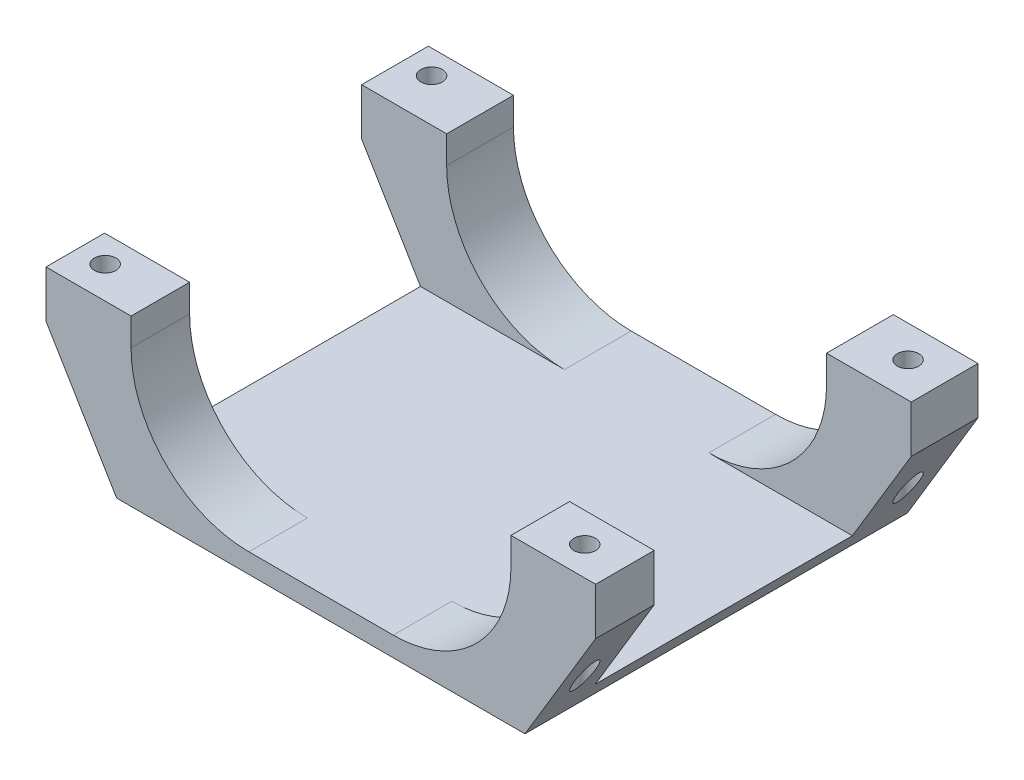
SolidWorks part; units mm, degrees
ref_plane "Front Plane" through (0, 0, 0) normal (0, 0, 1) x (1, 0, 0)
ref_plane "Top Plane" through (0, 0, 0) normal (0, 1, 0) x (1, 0, 0)
ref_plane "Right Plane" through (0, 0, 0) normal (1, 0, 0) x (0, 0, -1)
sketch "Sketch1" plane through (0, 0, 0) normal (0, 1, 0) x (1, 0, 0)
  line L1 (0, 0) -> (139.9914, 0)
  line L2 (0, 0) -> (0, 97.3933)
  line L3 (0, 97.3933) -> (139.9914, 97.3933)
  line L4 (139.9914, 0) -> (139.9914, 97.3933)
extrude "PiCover" add sketch "Sketch1" along normal blind 40 and the other way blind 2
sketch "Sketch2" plane through (0, 40, 0) normal (0, 1, 0) x (1, 0, 0)
  line L0 (139.9914, 97.3933) -> (0, 97.3933) construction
  line L1 (21.6644, 97.3933) -> (118.4243, 97.3933)
  line L2 (21.6644, 97.3933) -> (21.6644, -0.7263)
  line L3 (21.6644, -0.7263) -> (118.4243, -0.7263)
  line L4 (118.4243, 97.3933) -> (118.4243, -0.7263)
extrude "OpeningForPi" cut sketch "Sketch2" against normal blind 37
sketch "Sketch4" plane through (0, -2, 0) normal (0, -1, 0) x (1, 0, 0)
  line L0 (139.9914, -97.3933) -> (0, -97.3933) construction
  line L1 (139.9914, 0) -> (121.9914, 0)
  line L2 (139.9914, 0) -> (139.9914, -97.3933)
  line L3 (139.9914, -97.3933) -> (121.9914, -97.3933)
  line L4 (121.9914, 0) -> (121.9914, -97.3933)
  line L5 (0, 0) -> (139.9914, 0) construction
  line L6 (0, -97.3933) -> (18, -97.3933)
  line L7 (0, -97.3933) -> (0, 0)
  line L8 (0, 0) -> (18, 0)
  line L9 (18, -97.3933) -> (18, 0)
extrude "CutAwaysThatDefineScrewPlates" cut sketch "Sketch4" against normal blind 30
sketch "Sketch11" plane through (0, 0, 0) normal (0, 0, 1) x (1, 0, 0)
  line L0 (0, 28) -> (18, 28)
  line L1 (18, 28) -> (18, -2)
  line L2 (18, -2) -> (0, 28)
  line L3 (139.9914, 28) -> (121.9914, 28)
  line L4 (121.9914, 28) -> (121.9914, -2)
  line L5 (121.9914, -2) -> (139.9914, 28)
extrude "Boss-Extrude1" add sketch "Sketch11" against normal up to surface (97.3933 mm away) up to face at (70.0119, 22.8333, -97.3933)
sketch "Sketch6" plane through (21.6644, 0, 0) normal (1, 0, 0) x (0, 0, -1)
  line L0 (97.3933, 3) -> (0, 3) construction
  line L1 (80.3904, 3) -> (14.92, 3)
  line L2 (80.3904, 3) -> (80.3904, 40)
  line L3 (80.3904, 40) -> (14.92, 40)
  line L4 (14.92, 3) -> (14.92, 40)
  line L5 (97.3933, 40) -> (0, 40) construction
extrude "HoleForPowerHDMIAudio" cut sketch "Sketch6" against normal blind 30 and the other way blind 150
sketch "Sketch5" plane through (0, 40, 0) normal (0, 1, 0) x (1, 0, 0)
  circle A0 centre (129.6245, 49.8786) radius 2.75
sketch "Sketch7" plane through (0, 40, 0) normal (0, 1, 0) x (1, 0, 0)
  circle A0 centre (6.9345, 8.1289) radius 2.75
  circle A1 centre (6.9345, 91.2756) radius 2.75
  circle A2 centre (130.2887, 89.2742) radius 2.75
  circle A3 centre (129.8187, 7.3954) radius 2.75
extrude "Cut-Extrude7" cut sketch "Sketch7" against normal blind 60
fillet "Fillet1" radius 30 1 edges at (21.6644, 3, -88.8919)
fillet "Fillet2" radius 30 1 edges at (118.4243, 3, -88.8919)
fillet "Fillet3" radius 30 1 edges at (21.6644, 3, -7.46)
fillet "Fillet4" radius 30 1 edges at (118.4243, 3, -7.46)
